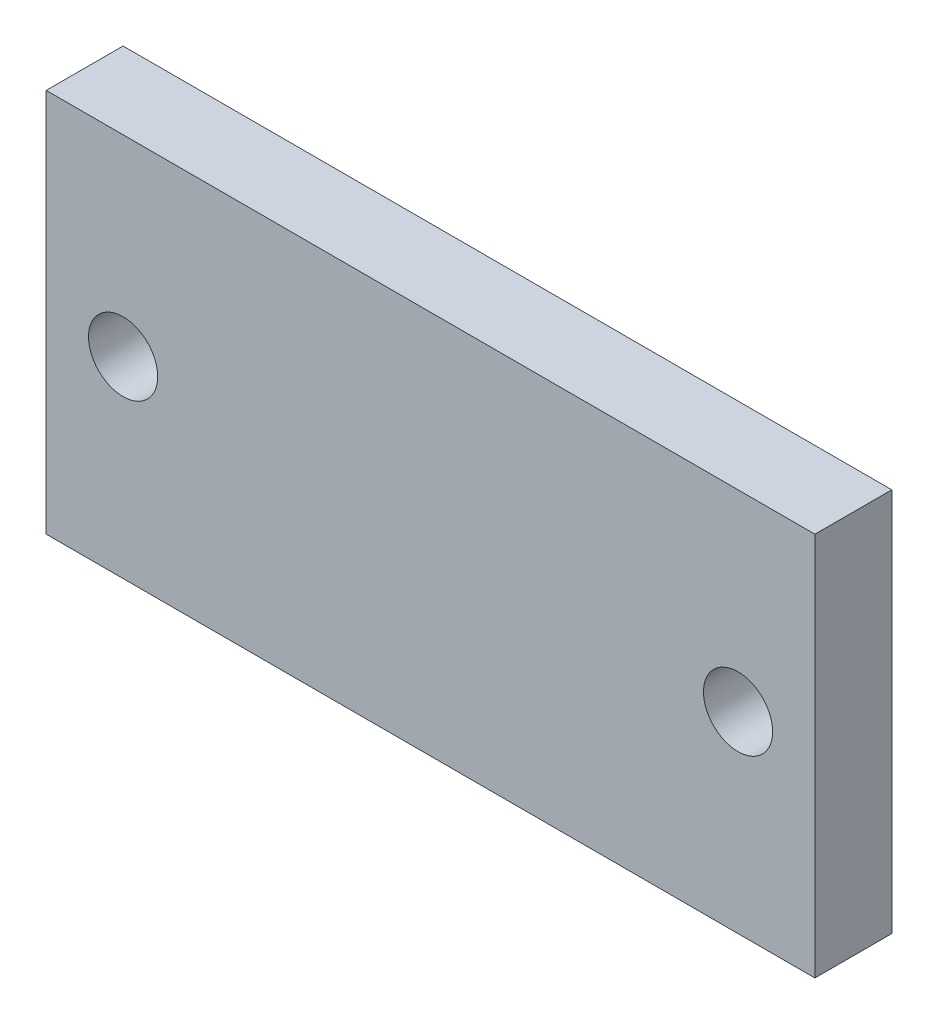
SolidWorks part; units mm, degrees
material "ABS"
ref_plane "Front Plane" through (0, 0, 0) normal (0, 0, 1) x (1, 0, 0)
ref_plane "Top Plane" through (0, 0, 0) normal (0, 1, 0) x (1, 0, 0)
ref_plane "Right Plane" through (0, 0, 0) normal (1, 0, 0) x (0, 0, -1)
sketch "Sketch1" plane through (0, 0, 0) normal (0, 0, 1) x (1, 0, 0)
  line L1 (0, 0) -> (50, 0)
  line L2 (0, 0) -> (0, 25)
  line L3 (0, 25) -> (50, 25)
  line L4 (50, 0) -> (50, 25)
  dimension "D1" = 25
  dimension "D2" = 50
extrude "Boss-Extrude1" add sketch "Sketch1" along normal blind 5
hole_wizard "M4 Clearance Hole1" positions "Sketch2" profile "Sketch4" hole size "M4" standard "ANSI Metric" end condition up to next
sketch "Sketch2" plane through (0, 0, 5) normal (0, 0, 1) x (1, 0, 0)
  line L0 (0, 25) -> (0, 0) construction
  line L1 (50, 0) -> (50, 25) construction
  point P0 (5, 12.5)
  point P2 (45, 12.5)
  point P6 (0, 0)
  point P9 (0, 12.5)
  dimension "D1" = 5
  dimension "D2" = 5
sketch "Sketch4" plane through (5, 12.5, 5) normal (1, 0, 0) x (0, -1, 0)
  line L0 (0, 0) -> (0, 5)
  line L1 (0, 5) -> (2.25, 5)
  line L2 (2.25, 5) -> (2.25, 0)
  line L5 (2.25, 0) -> (0, 0)
  line L11 (0, -6.35) -> (0, 107.95) construction
  dimension "Thru Hole Dia." = 4.5
  dimension "Thru Hole Depth" = 5
